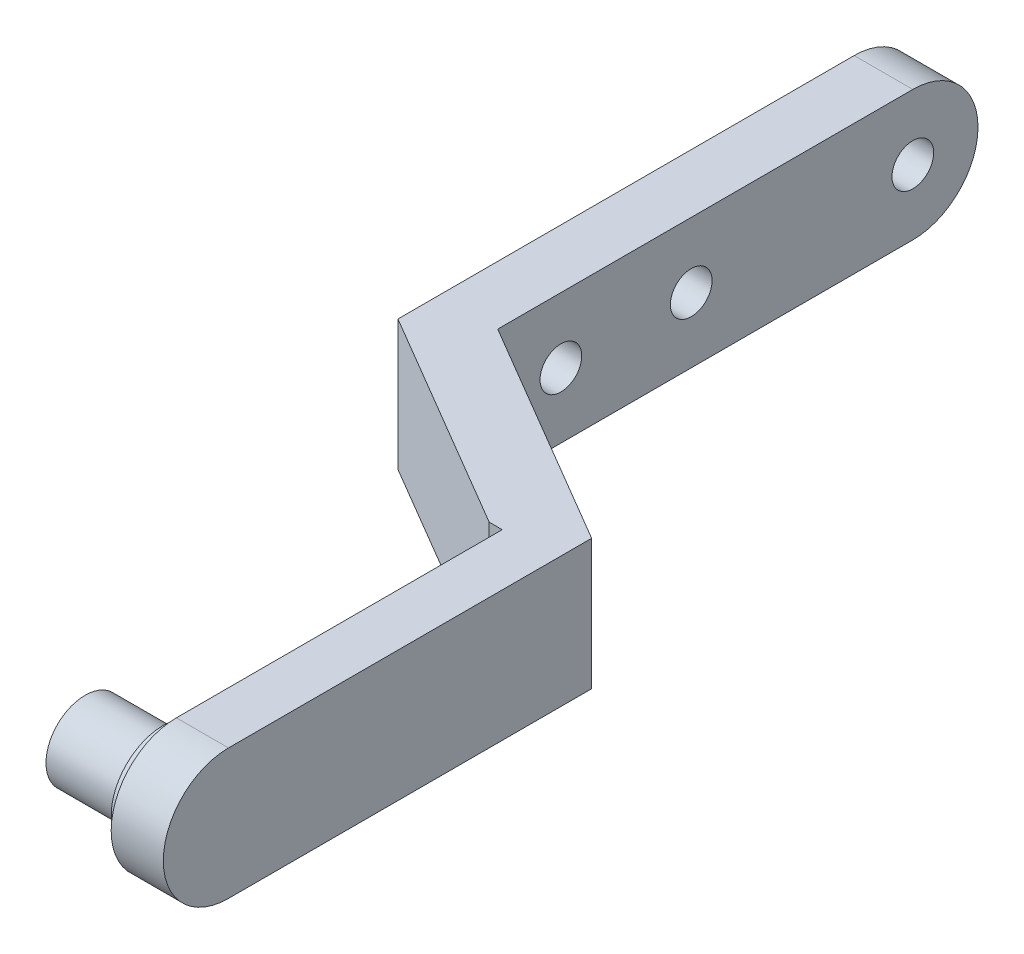
SolidWorks part; units mm, degrees
ref_plane "Front Plane" through (0, 0, 0) normal (0, 0, 1) x (1, 0, 0)
ref_plane "Top Plane" through (0, 0, 0) normal (0, 1, 0) x (1, 0, 0)
ref_plane "Right Plane" through (0, 0, 0) normal (1, 0, 0) x (0, 0, -1)
other "Configuration Table"
sketch "草图2" plane through (0, 0, 0) normal (0, 1, 0) x (1, 0, 0)
  line L0 (-17, 40) -> (0, 30)
  line L2 (5, 32.8597) -> (5, 0)
  line L3 (5, 0) -> (0, 0)
  line L4 (0, 30) -> (0, 0)
  line L5 (-17, 80) -> (-12.5, 80)
  line L6 (-17, 80) -> (-17, 40)
  line L8 (-12.5, 80) -> (-12.5, 43.1538)
  line L9 (-12.5, 43.1538) -> (5, 32.8597)
  point P2 (0, 0)
  point P10 (5, 40)
  point P11 (5, 40)
  point P12 (5, 42.1444)
  dimension "D1" = 5
  dimension "D2" = 4.5
  dimension "D3" = 80
  dimension "D4" = 40
  dimension "D5" = 30
  dimension "D6" = 17
  dimension "D7" = 5
extrude "凸台-拉伸2" add sketch "草图2" along normal mid plane 10
sketch "草图3" plane through (-12.5, 0, 0) normal (1, 0, 0) x (0, 0, -1)
  line L0 (5, 0) -> (75, 0) construction
  line L1 (5, 5) -> (75, 5)
  line L2 (5, -5) -> (75, -5)
  line L3 (80, 5) -> (80, -5) construction
  line L4 (32.8597, 5) -> (43.1538, 5) construction
  arc A0 (5, 5) -> (5, -5) centre (5, 0) ccw
  arc A1 (75, -5) -> (75, 5) centre (75, 0) ccw
  point P3 (40, 0)
extrude "切除-拉伸1" cut sketch "草图3" against normal through all both and the other way through all flip side to cut
sketch "草图4" plane through (5, 0, 0) normal (1, 0, 0) x (0, 0, -1)
  circle A0 centre (75, 0) radius 1.6
  circle A1 centre (58, 0) radius 1.6
  circle A2 centre (48, 0) radius 1.6
  point P7 (0, 0)
  dimension "D1" = 3.2
  dimension "D2" = 3.2
  dimension "D3" = 3.2
  dimension "D4" = 17
  dimension "D5" = 10
extrude "切除-拉伸2" cut sketch "草图4" against normal through all both and the other way through all
sketch "草图5" plane through (0, 0, 0) normal (-1, 0, 0) x (0, 0, 1)
  circle A0 centre (-5, 0) radius 3
  arc A1 (-5, -5) -> (-5, 5) centre (-5, 0) ccw construction
  dimension "D1" = 6
extrude "凸台-拉伸4" add sketch "草图5" along normal blind 6
sketch "草图6" plane through (0, 0, 0) normal (-1, 0, 0) x (0, 0, 1)
  line L3 (-5, 5) -> (-30, 5)
  line L4 (-30, 5) -> (-30, -5)
  line L5 (-30, -5) -> (-5, -5)
  line L6 (-5, 5) -> (-30, 5)
  line L7 (-30, 5) -> (-30, -5)
  line L8 (-30, -5) -> (-5, -5)
  circle A0 centre (-5, 0) radius 4
  arc A2 (-5, -5) -> (-5, 5) centre (-5, 0) ccw
  arc A3 (-5, -5) -> (-5, 5) centre (-5, 0) ccw
  dimension "D1" = 8
  dimension "D2" = 0
extrude "切除-拉伸3" cut sketch "草图6" against normal blind 1 and the other way through all
